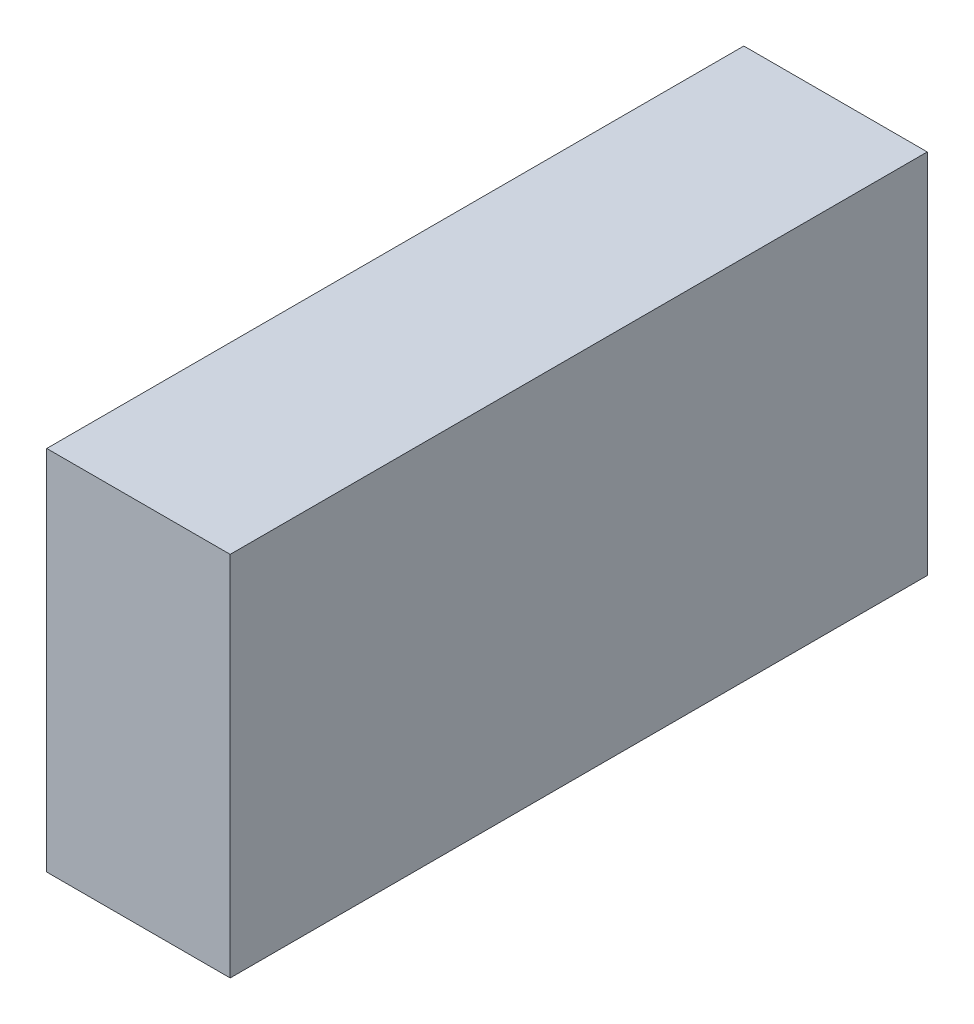
SolidWorks part; units mm, degrees
ref_plane "Front Plane" through (0, 0, 0) normal (0, 0, 1) x (1, 0, 0)
ref_plane "Top Plane" through (0, 0, 0) normal (0, 1, 0) x (1, 0, 0)
ref_plane "Right Plane" through (0, 0, 0) normal (1, 0, 0) x (0, 0, -1)
sketch "Sketch1" plane through (0, 0, 0) normal (1, 0, 0) x (0, 0, -1)
  line L1 (0, 0) -> (48.26, 0)
  line L2 (0, 0) -> (0, 25.4)
  line L3 (0, 25.4) -> (48.26, 25.4)
  line L4 (48.26, 0) -> (48.26, 25.4)
  dimension "D1" = 48.26
  dimension "D2" = 25.4
extrude "Boss-Extrude1" add sketch "Sketch1" along normal blind 12.7
